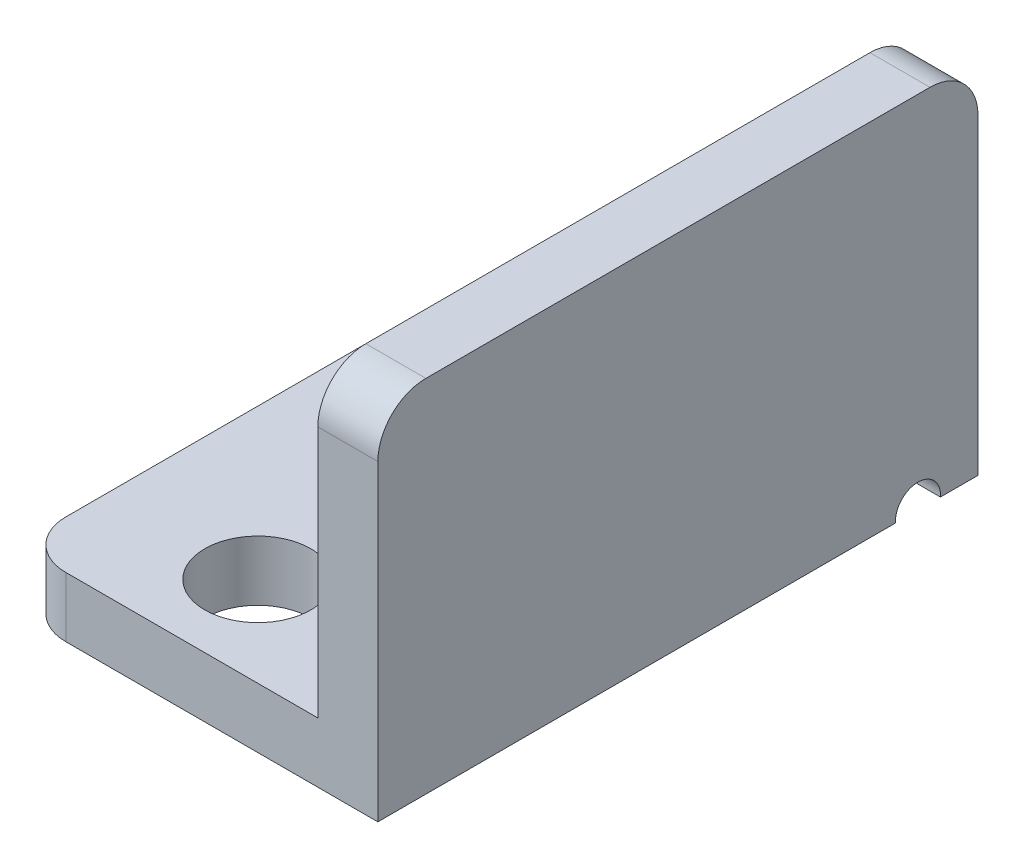
SolidWorks part; units mm, degrees
material "6061 Alloy"
ref_plane "Front" through (0, 0, 0) normal (0, 0, 1) x (1, 0, 0)
ref_plane "Top" through (0, 0, 0) normal (0, 1, 0) x (1, 0, 0)
ref_plane "Right" through (0, 0, 0) normal (1, 0, 0) x (0, 0, -1)
sketch "Sketch1" plane through (0, 0, 0) normal (0, 0, 1) x (1, 0, 0)
  line L0 (0, 0) -> (0, 19.05)
  line L1 (0, 19.05) -> (-3.175, 19.05)
  line L2 (-3.175, 19.05) -> (-3.175, 3.175)
  line L3 (-3.175, 3.175) -> (-19.05, 3.175)
  line L4 (-19.05, 3.175) -> (-19.05, 0)
  line L5 (-19.05, 0) -> (0, 0)
  dimension "D1" = 19.05
  dimension "D2" = 3.175
extrude "Boss-Extrude1" add sketch "Sketch1" along normal blind 31.75
hole_wizard "3/32 (0.09375) Diameter Hole1" positions "Sketch2" profile "Sketch3" hole size "3/32" standard "ANSI Inch"
sketch "Sketch2" plane through (0, 0, 0) normal (1, 0, 0) x (0, 0, -1)
  line L2 (-3.175, 0.0889) -> (0, 0.0889) construction
  line L3 (0, 0) -> (0, 19.05) construction
  line L4 (0, 0.0889) -> (3.175, 0.0889) construction
  line L6 (-31.75, 0) -> (0, 0) construction
  line L7 (-31.75, -6.35) -> (0, -6.35) construction
  line L9 (-31.75, 0) -> (-31.75, 19.05) construction
  circle A0 centre (-3.175, 0.0889) radius 2.9464 construction
  circle A1 centre (3.175, 0.0889) radius 2.9464 construction
  point P1 (-3.175, 0.0889)
  point P28 (0, 0)
  dimension "D1" = 5.8928
  dimension "D2" = 6.35
  dimension "D3" = 6.4389
  dimension "D4" = 6.35
sketch "Sketch3" plane through (0, 0.0889, 3.175) normal (0, 1, 0) x (0, 0, -1)
  line L0 (0, 0) -> (0, 26.1154)
  line L1 (0, 26.1154) -> (1.1906, 25.4)
  line L2 (1.1906, 25.4) -> (1.1906, 0)
  line L5 (1.1906, 0) -> (0, 0)
  line L10 (0, 26.1154) -> (-1.1906, 25.4) construction
  line L11 (0, -6.35) -> (0, 107.95) construction
  dimension "Hole Dia." = 2.3812
  dimension "Hole Depth" = 25.4
  dimension "Drill Angle" = 118
hole_wizard "#10 Clearance Hole1" positions "Sketch4" profile "Sketch5" hole size "#10" standard "ANSI Inch"
sketch "Sketch4" plane through (0, 3.175, 0) normal (0, 1, 0) x (1, 0, 0)
  line L0 (-11.1125, 0) -> (-11.1125, -31.75) construction
  line L1 (-3.175, 0) -> (-19.05, 0) construction
  line L2 (-3.175, -31.75) -> (-19.05, -31.75) construction
  point P8 (-11.1125, -4.7625)
  point P10 (-11.1125, -26.9875)
  point P15 (-11.1125, -15.875)
  dimension "D1" = 11.1125
  dimension "D2" = 11.1125
sketch "Sketch5" plane through (-11.1125, 3.175, 26.9875) normal (1, 0, 0) x (0, 0, 1)
  line L0 (0, 0) -> (0, 27.0864)
  line L1 (0, 27.0864) -> (2.8067, 25.4)
  line L2 (2.8067, 25.4) -> (2.8067, 0)
  line L5 (2.8067, 0) -> (0, 0)
  line L10 (0, 27.0864) -> (-2.8067, 25.4) construction
  line L11 (0, -6.35) -> (0, 107.95) construction
  dimension "Hole Dia." = 5.6134
  dimension "Hole Depth" = 25.4
  dimension "Drill Angle" = 118
fillet "Fillet1" radius 2.54 4 edges at (-1.5875, 19.05, 31.75) (-1.5875, 19.05, 0) (-19.05, 1.5875, 31.75) (-19.05, 1.5875, 0)
mirror "Mirror2" [suppressed]
delete or keep bodies "Body-Delete/Keep 1" [suppressed] type delete bodies bodies 103
